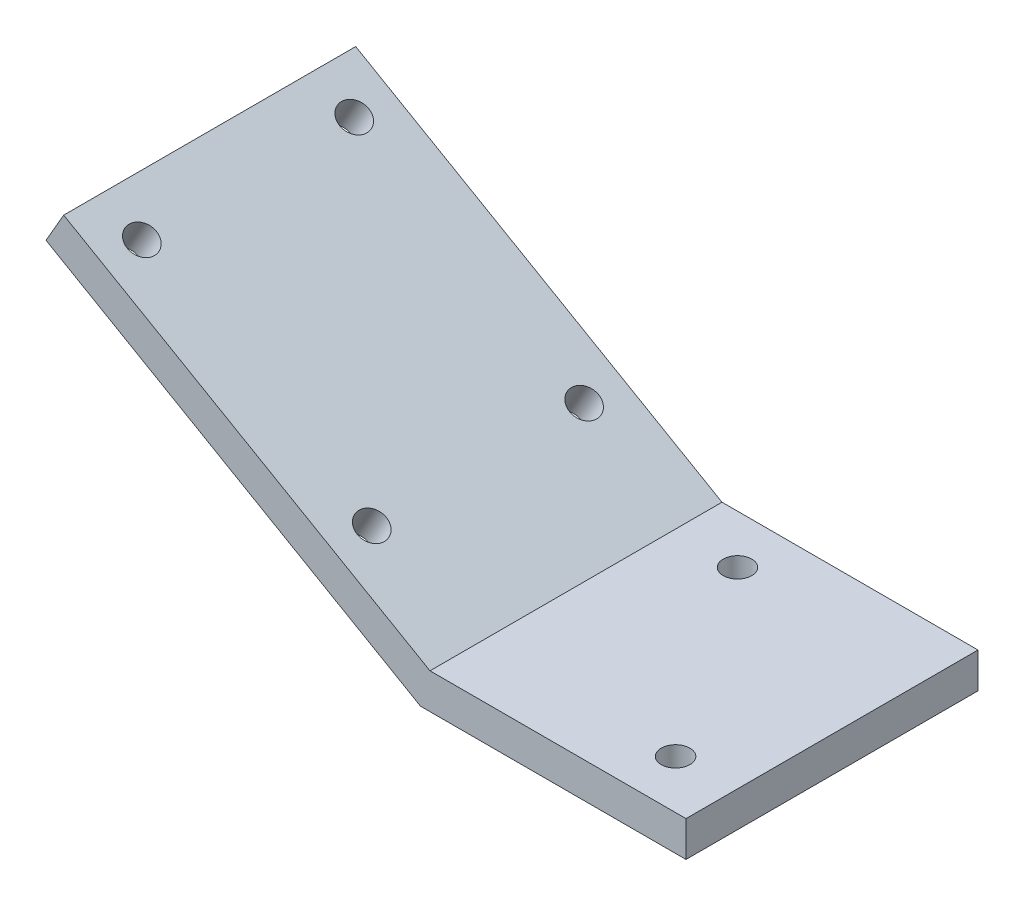
SolidWorks part; units mm, degrees
ref_plane "Front Plane" through (0, 0, 0) normal (0, 0, 1) x (1, 0, 0)
ref_plane "Top Plane" through (0, 0, 0) normal (0, 1, 0) x (1, 0, 0)
ref_plane "Right Plane" through (0, 0, 0) normal (1, 0, 0) x (0, 0, -1)
sketch "Sketch1" plane through (0, 0, 0) normal (0, 1, 0) x (1, 0, 0)
  line L1 (-25, 11.5) -> (25, 11.5)
  line L2 (-25, 11.5) -> (-25, -11.5)
  line L3 (-25, -11.5) -> (25, -11.5)
  line L4 (25, 11.5) -> (25, -11.5)
  line L5 (-25, 11.5) -> (25, -11.5) construction
  line L6 (-25, -11.5) -> (25, 11.5) construction
  point P0 (0, 0)
  dimension "D1" = 23
  dimension "D2" = 50
extrude "Boss-Extrude1" add sketch "Sketch1" along normal blind 20
sketch "Sketch2" plane through (0, 0, 11.5) normal (0, 0, 1) x (1, 0, 0)
  line L0 (25, 4) -> (1.0718, 4)
  line L1 (25, 20) -> (25, 0) construction
  line L2 (1.0718, 4) -> (-25, 19.0526)
  line L3 (-25, 20) -> (-25, 0) construction
  line L4 (-25, 0) -> (25, 0) construction
  line L5 (-25, 0) -> (0, 0)
  line L6 (-25, 14.4338) -> (0, 0)
  line L7 (-25, 19.0526) -> (-25, 20)
  line L8 (-25, 20) -> (25, 20)
  line L9 (25, 20) -> (25, 4)
  line L10 (-25, 20) -> (-25, 19.0526)
  line L11 (-25, 14.4338) -> (-25, 0)
  dimension "D1" = 150
  dimension "D2" = 4
  dimension "D5" = 0
extrude "Cut-Extrude3" cut sketch "Sketch2" against normal blind 30
sketch "Sketch4" plane through (0, 0, 11.5) normal (0, 0, 1) x (1, 0, 0)
  line L0 (-25, 14.4338) -> (-23, 17.8979)
  line L1 (1.0718, 4) -> (-25, 19.0526) construction
  line L2 (-25, 14.4338) -> (0, 0) construction
  line L3 (-23, 17.8979) -> (-25, 19.0526)
  line L4 (-25, 19.0526) -> (-25, 14.4338)
  dimension "D1" = 90
extrude "Cut-Extrude4" cut sketch "Sketch4" against normal blind 30
sketch "Sketch9" plane through (-25, 14.4338, 0) normal (-0.866, 0.5, 0) x (0, 0, 1)
  line L0 (-11.5, 4) -> (11.5, 4)
  line L1 (11.5, 4) -> (11.5, 0)
  line L2 (11.5, 0) -> (-11.5, 0)
  line L3 (-11.5, 0) -> (-11.5, 4)
extrude "Boss-Extrude2" add sketch "Sketch9" along normal blind 20
sketch "Sketch11" plane through (0, 0, -11.5) normal (0, 0, -1) x (-1, 0, 0)
  line L0 (-25, 4) -> (-1.0718, 4)
  line L1 (-1.0718, 4) -> (40.3205, 27.8979)
  line L2 (40.3205, 27.8979) -> (42.3205, 24.4338)
  line L3 (42.3205, 24.4338) -> (0, 0)
  line L4 (0, 0) -> (-25, 0)
  line L5 (-25, 0) -> (-25, 4)
extrude "Boss-Extrude3" add sketch "Sketch11" along normal blind 10
sketch "Sketch14" plane through (2, 3.4641, 0) normal (0.5, 0.866, 0) x (0.866, -0.5, 0)
  circle A0 centre (-43.8675, 17) radius 1.65
  circle A1 centre (-43.8675, -7) radius 1.65
  circle A2 centre (-13.8675, 17) radius 1.65
  circle A3 centre (-13.8675, -7) radius 1.65
  dimension "D1" = 3.3
  dimension "D2" = 3.3
  dimension "D3" = 3.3
  dimension "D4" = 3.3
  dimension "D5" = 30
extrude "Cut-Extrude6" cut sketch "Sketch14" against normal blind 10
sketch "Sketch17" plane through (0, 0, -21.5) normal (0, 0, -1) x (-1, 0, 0)
  line L0 (2.1062, 5.8348) -> (4.1062, 2.3707)
  line L1 (40.3205, 27.8979) -> (-1.0718, 4) construction
  line L2 (0, 0) -> (42.3205, 24.4338) construction
  line L3 (4.1062, 2.3707) -> (-16.99, -10.6506)
  line L4 (-16.99, -10.6506) -> (-27.424, -10.6506)
  line L5 (-27.424, -10.6506) -> (-28.8305, 8.5324)
  line L6 (-28.8305, 8.5324) -> (-0.4365, 9.7305)
  line L7 (-0.4365, 9.7305) -> (2.1062, 5.8348)
sketch "Sketch18" plane through (2, 3.4641, 0) normal (0.5, 0.866, 0) x (0.866, -0.5, 0)
  line L0 (-13.8675, 17) -> (-8.8675, 17)
  line L1 (-8.8675, 21.5) -> (-8.8675, -11.9289)
  line L2 (-48.8675, 21.5) -> (-1.0718, 21.5) construction
  line L3 (-8.8675, -11.9289) -> (-0.7836, -11.9289)
  line L4 (-0.7836, -11.9289) -> (-0.7836, 24.3364)
  line L5 (-0.7836, 24.3364) -> (-9.3377, 24.3364)
  line L6 (-9.3377, 24.3364) -> (-8.8675, 21.5)
  dimension "D1" = 5
sketch "Sketch22" plane through (25, 0, 0) normal (1, 0, 0) x (0, 0, -1)
  line L0 (-11.5, 4) -> (21.5, 4)
  line L1 (21.5, 4) -> (21.5, 0)
  line L2 (21.5, 0) -> (-11.5, 0)
  line L3 (-11.5, 0) -> (-11.5, 4)
extrude "Boss-Extrude4" add sketch "Sketch22" along normal blind 5
sketch "Sketch23" plane through (0, 0, 0) normal (0, -1, 0) x (1, 0, 0)
  line L0 (0, -5) -> (30, -5) construction
  line L1 (0, -21.5) -> (0, 11.5) construction
  line L2 (30, 11.5) -> (30, -21.5) construction
  line L3 (27.6222, -20.3) -> (27.6222, 10.3)
  line L4 (27.6222, 10.3) -> (4.0222, 10.3)
  line L5 (4.0222, 10.3) -> (4.0222, -20.3)
  line L6 (27.6222, -20.3) -> (4.0222, -20.3)
  line L7 (27.6222, 6) -> (23.3222, 6)
  line L8 (23.3222, 6) -> (23.3222, 10.3)
  line L9 (4.0222, -16) -> (8.3222, -16)
  line L10 (8.3222, -16) -> (8.3222, -20.3)
  circle A0 centre (23.3222, 6) radius 1.62
  circle A1 centre (8.3222, -16) radius 1.62
  point P11 (27.6222, -5)
  point P12 (4.0222, -5)
  dimension "D7" = 3.24
  dimension "D8" = 3.24
  dimension "D1" = 23.6
  dimension "D2" = 15.3
  dimension "D3" = 4.3
  dimension "D4" = 4.3
  dimension "D5" = 4.3
  dimension "D6" = 4.3
extrude "Cut-Extrude7" cut sketch "Sketch23" against normal blind 5 contours L8 A0 L7 | L7 A0 L8 | L10 A1 L9 | L9 A1 L10
